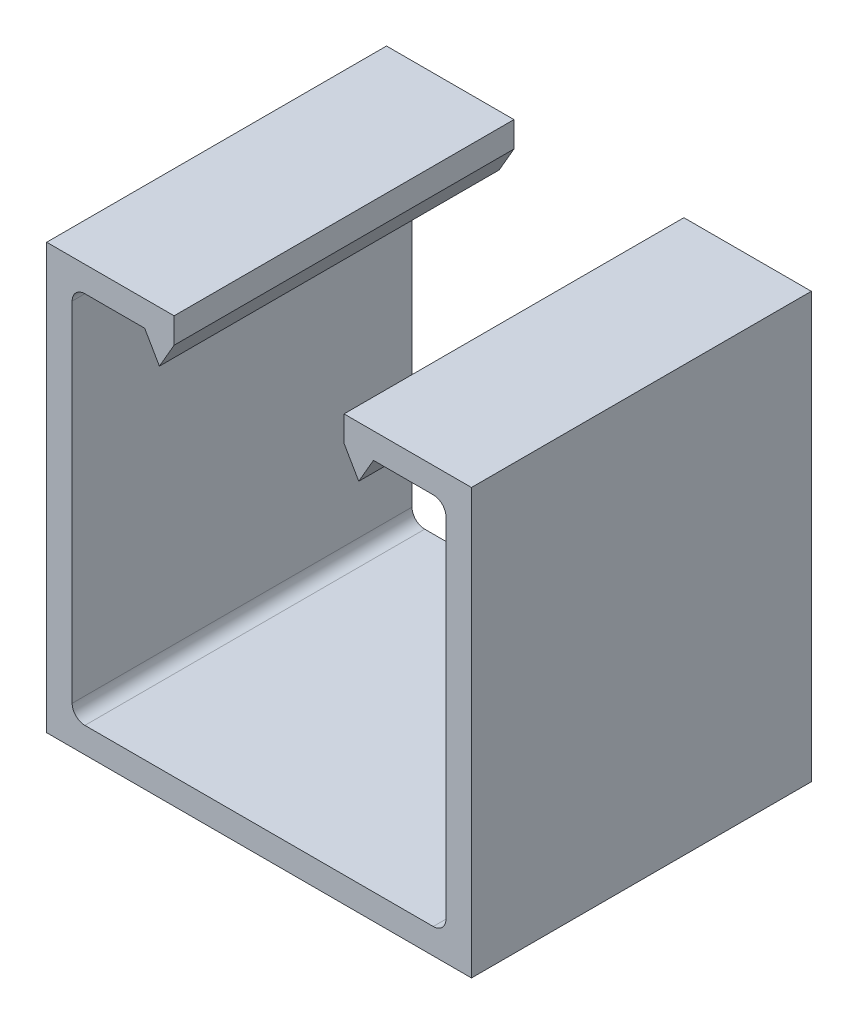
SolidWorks part; units mm, degrees
ref_plane "Plane1" through (0, 0, 0) normal (0, 0, 1) x (1, 0, 0)
ref_plane "Plane2" through (0, 0, 0) normal (0, 1, 0) x (1, 0, 0)
ref_plane "Plane3" through (0, 0, 0) normal (1, 0, 0) x (0, 0, -1)
sketch "Sketch1" plane through (0, 0, 0) normal (0, 0, 1) x (1, 0, 0)
  line L0 (-6.35, 15.875) -> (-15.875, 15.875)
  line L1 (-15.875, 15.875) -> (-15.875, -15.875)
  line L2 (-15.875, -15.875) -> (15.875, -15.875)
  line L3 (15.875, -15.875) -> (15.875, 15.875)
  line L4 (15.875, 15.875) -> (6.35, 15.875)
  line L5 (13.0175, 13.97) -> (8.5497, 13.97)
  line L6 (13.97, -13.0175) -> (13.97, 13.0175)
  line L7 (-13.0175, -13.97) -> (13.0175, -13.97)
  line L8 (-13.97, 13.0175) -> (-13.97, -13.0175)
  line L9 (-8.5497, 13.97) -> (-13.0175, 13.97)
  line L10 (8.5497, 13.97) -> (7.4499, 12.065)
  line L11 (7.4499, 12.065) -> (6.35, 13.97)
  line L12 (6.35, 13.97) -> (6.35, 15.875)
  line L13 (-8.5497, 13.97) -> (-7.4499, 12.065)
  line L14 (-7.4499, 12.065) -> (-6.35, 13.97)
  line L15 (-6.35, 13.97) -> (-6.35, 15.875)
  arc A0 (-13.97, -13.0175) -> (-13.0175, -13.97) centre (-13.0175, -13.0175) ccw
  arc A1 (-13.0175, 13.97) -> (-13.97, 13.0175) centre (-13.0175, 13.0175) ccw
  arc A2 (13.97, 13.0175) -> (13.0175, 13.97) centre (13.0175, 13.0175) ccw
  arc A3 (13.0175, -13.97) -> (13.97, -13.0175) centre (13.0175, -13.0175) ccw
  dimension "D5" = 0.9525
  dimension "Width" = 31.75
  dimension "Height" = 31.75
  dimension "D8" = 15.875
  dimension "D9" = 15.875
  dimension "D10" = 12.7
  dimension "edge" = 9.525
  dimension "D13" = 1.0999
  dimension "D4" = 60
extrude "Base-Extrude" add sketch "Sketch1" along normal mid plane 25.4
equation "\"D8@Sketch1\" = \"Width@Sketch1\" / 2"
equation "\"D9@Sketch1\" = \"Height@Sketch1\" / 2"
equation "\"D10@Sketch1\" = \"Width@Sketch1\" - 2 * \"edge@Sketch1\""
equation "\"D5@Sketch1\" = \"gauge@Sketch1\" / 2"
equation "\"D13@Sketch1\" = \"gauge@Sketch1\" * .577350269"
